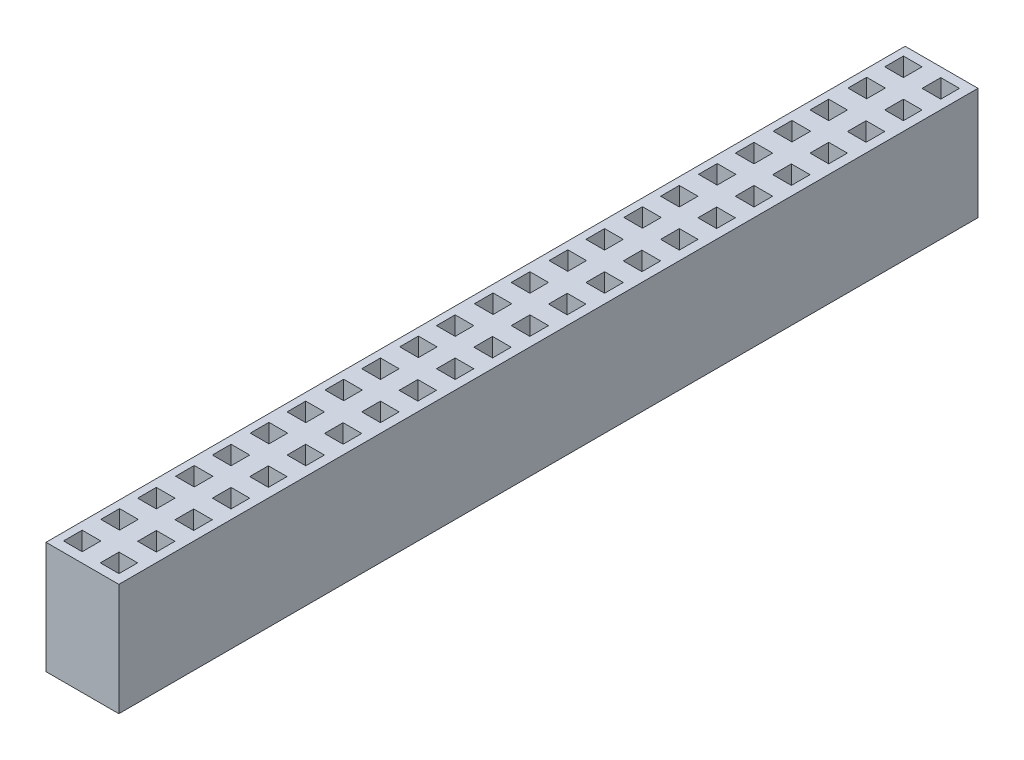
SolidWorks part; units mm, degrees
ref_plane "Front Plane" through (0, 0, 0) normal (0, 0, 1) x (1, 0, 0)
ref_plane "Top Plane" through (0, 0, 0) normal (0, 1, 0) x (1, 0, 0)
ref_plane "Right Plane" through (0, 0, 0) normal (1, 0, 0) x (0, 0, -1)
sketch "Sketch1" plane through (0, 0, 0) normal (0, 1, 0) x (1, 0, 0)
  line L0 (3.0564, 57.785) -> (4.3264, 57.785)
  line L1 (0, 0) -> (4.953, 0)
  line L2 (0, 0) -> (0, 58.42)
  line L3 (0, 58.42) -> (4.953, 58.42)
  line L4 (4.953, 0) -> (4.953, 58.42)
  line L5 (0.5164, 57.785) -> (1.7864, 57.785)
  line L6 (0.5164, 57.785) -> (0.5164, 56.515)
  line L7 (0.5164, 56.515) -> (1.7864, 56.515)
  line L8 (1.7864, 57.785) -> (1.7864, 56.515)
  line L9 (3.0564, 57.785) -> (3.0564, 56.515)
  line L10 (3.0564, 56.515) -> (4.3264, 56.515)
  line L11 (4.3264, 57.785) -> (4.3264, 56.515)
  line L12 (3.0564, 55.245) -> (4.3264, 55.245)
  line L13 (0.5164, 55.2839) -> (1.7864, 55.2839)
  line L14 (0.5164, 55.2839) -> (0.5164, 54.0139)
  line L15 (0.5164, 54.0139) -> (1.7864, 54.0139)
  line L16 (1.7864, 55.2839) -> (1.7864, 54.0139)
  line L17 (3.0564, 55.245) -> (3.0564, 53.975)
  line L18 (3.0564, 53.975) -> (4.3264, 53.975)
  line L19 (4.3264, 55.245) -> (4.3264, 53.975)
  line L20 (3.0564, 52.705) -> (4.3264, 52.705)
  line L21 (0.5164, 52.705) -> (1.7864, 52.705)
  line L22 (0.5164, 52.705) -> (0.5164, 51.435)
  line L23 (0.5164, 51.435) -> (1.7864, 51.435)
  line L24 (1.7864, 52.705) -> (1.7864, 51.435)
  line L25 (3.0564, 52.705) -> (3.0564, 51.435)
  line L26 (3.0564, 51.435) -> (4.3264, 51.435)
  line L27 (4.3264, 52.705) -> (4.3264, 51.435)
  line L28 (3.0564, 50.165) -> (4.3264, 50.165)
  line L29 (0.5164, 50.2039) -> (1.7864, 50.2039)
  line L30 (0.5164, 50.2039) -> (0.5164, 48.9339)
  line L31 (0.5164, 48.9339) -> (1.7864, 48.9339)
  line L32 (1.7864, 50.2039) -> (1.7864, 48.9339)
  line L33 (3.0564, 50.165) -> (3.0564, 48.895)
  line L34 (3.0564, 48.895) -> (4.3264, 48.895)
  line L35 (4.3264, 50.165) -> (4.3264, 48.895)
  line L36 (3.0564, 47.625) -> (4.3264, 47.625)
  line L37 (0.5164, 47.625) -> (1.7864, 47.625)
  line L38 (0.5164, 47.625) -> (0.5164, 46.355)
  line L39 (0.5164, 46.355) -> (1.7864, 46.355)
  line L40 (1.7864, 47.625) -> (1.7864, 46.355)
  line L41 (3.0564, 47.625) -> (3.0564, 46.355)
  line L42 (3.0564, 46.355) -> (4.3264, 46.355)
  line L43 (4.3264, 47.625) -> (4.3264, 46.355)
  line L44 (3.0564, 45.085) -> (4.3264, 45.085)
  line L45 (0.5164, 45.1239) -> (1.7864, 45.1239)
  line L46 (0.5164, 45.1239) -> (0.5164, 43.8539)
  line L47 (0.5164, 43.8539) -> (1.7864, 43.8539)
  line L48 (1.7864, 45.1239) -> (1.7864, 43.8539)
  line L49 (3.0564, 45.085) -> (3.0564, 43.815)
  line L50 (3.0564, 43.815) -> (4.3264, 43.815)
  line L51 (4.3264, 45.085) -> (4.3264, 43.815)
  line L52 (3.0564, 42.545) -> (4.3264, 42.545)
  line L53 (0.5164, 42.545) -> (1.7864, 42.545)
  line L54 (0.5164, 42.545) -> (0.5164, 41.275)
  line L55 (0.5164, 41.275) -> (1.7864, 41.275)
  line L56 (1.7864, 42.545) -> (1.7864, 41.275)
  line L57 (3.0564, 42.545) -> (3.0564, 41.275)
  line L58 (3.0564, 41.275) -> (4.3264, 41.275)
  line L59 (4.3264, 42.545) -> (4.3264, 41.275)
  line L60 (3.0564, 40.005) -> (4.3264, 40.005)
  line L61 (0.5164, 40.0439) -> (1.7864, 40.0439)
  line L62 (0.5164, 40.0439) -> (0.5164, 38.7739)
  line L63 (0.5164, 38.7739) -> (1.7864, 38.7739)
  line L64 (1.7864, 40.0439) -> (1.7864, 38.7739)
  line L65 (3.0564, 40.005) -> (3.0564, 38.735)
  line L66 (3.0564, 38.735) -> (4.3264, 38.735)
  line L67 (4.3264, 40.005) -> (4.3264, 38.735)
  line L68 (3.0564, 37.465) -> (4.3264, 37.465)
  line L69 (0.5164, 37.465) -> (1.7864, 37.465)
  line L70 (0.5164, 37.465) -> (0.5164, 36.195)
  line L71 (0.5164, 36.195) -> (1.7864, 36.195)
  line L72 (1.7864, 37.465) -> (1.7864, 36.195)
  line L73 (3.0564, 37.465) -> (3.0564, 36.195)
  line L74 (3.0564, 36.195) -> (4.3264, 36.195)
  line L75 (4.3264, 37.465) -> (4.3264, 36.195)
  line L76 (3.0564, 34.925) -> (4.3264, 34.925)
  line L77 (0.5164, 34.9639) -> (1.7864, 34.9639)
  line L78 (0.5164, 34.9639) -> (0.5164, 33.6939)
  line L79 (0.5164, 33.6939) -> (1.7864, 33.6939)
  line L80 (1.7864, 34.9639) -> (1.7864, 33.6939)
  line L81 (3.0564, 34.925) -> (3.0564, 33.655)
  line L82 (3.0564, 33.655) -> (4.3264, 33.655)
  line L83 (4.3264, 34.925) -> (4.3264, 33.655)
  line L84 (3.0564, 32.385) -> (4.3264, 32.385)
  line L85 (0.5164, 32.385) -> (1.7864, 32.385)
  line L86 (0.5164, 32.385) -> (0.5164, 31.115)
  line L87 (0.5164, 31.115) -> (1.7864, 31.115)
  line L88 (1.7864, 32.385) -> (1.7864, 31.115)
  line L89 (3.0564, 32.385) -> (3.0564, 31.115)
  line L90 (3.0564, 31.115) -> (4.3264, 31.115)
  line L91 (4.3264, 32.385) -> (4.3264, 31.115)
  line L92 (3.0564, 29.845) -> (4.3264, 29.845)
  line L93 (0.5164, 29.8839) -> (1.7864, 29.8839)
  line L94 (0.5164, 29.8839) -> (0.5164, 28.6139)
  line L95 (0.5164, 28.6139) -> (1.7864, 28.6139)
  line L96 (1.7864, 29.8839) -> (1.7864, 28.6139)
  line L97 (3.0564, 29.845) -> (3.0564, 28.575)
  line L98 (3.0564, 28.575) -> (4.3264, 28.575)
  line L99 (4.3264, 29.845) -> (4.3264, 28.575)
  line L100 (3.0564, 27.305) -> (4.3264, 27.305)
  line L101 (0.5164, 27.305) -> (1.7864, 27.305)
  line L102 (0.5164, 27.305) -> (0.5164, 26.035)
  line L103 (0.5164, 26.035) -> (1.7864, 26.035)
  line L104 (1.7864, 27.305) -> (1.7864, 26.035)
  line L105 (3.0564, 27.305) -> (3.0564, 26.035)
  line L106 (3.0564, 26.035) -> (4.3264, 26.035)
  line L107 (4.3264, 27.305) -> (4.3264, 26.035)
  line L108 (3.0564, 24.765) -> (4.3264, 24.765)
  line L109 (0.5164, 24.8039) -> (1.7864, 24.8039)
  line L110 (0.5164, 24.8039) -> (0.5164, 23.5339)
  line L111 (0.5164, 23.5339) -> (1.7864, 23.5339)
  line L112 (1.7864, 24.8039) -> (1.7864, 23.5339)
  line L113 (3.0564, 24.765) -> (3.0564, 23.495)
  line L114 (3.0564, 23.495) -> (4.3264, 23.495)
  line L115 (4.3264, 24.765) -> (4.3264, 23.495)
  line L116 (3.0564, 22.225) -> (4.3264, 22.225)
  line L117 (0.5164, 22.225) -> (1.7864, 22.225)
  line L118 (0.5164, 22.225) -> (0.5164, 20.955)
  line L119 (0.5164, 20.955) -> (1.7864, 20.955)
  line L120 (1.7864, 22.225) -> (1.7864, 20.955)
  line L121 (3.0564, 22.225) -> (3.0564, 20.955)
  line L122 (3.0564, 20.955) -> (4.3264, 20.955)
  line L123 (4.3264, 22.225) -> (4.3264, 20.955)
  line L124 (3.0564, 19.685) -> (4.3264, 19.685)
  line L125 (0.5164, 19.7239) -> (1.7864, 19.7239)
  line L126 (0.5164, 19.7239) -> (0.5164, 18.4539)
  line L127 (0.5164, 18.4539) -> (1.7864, 18.4539)
  line L128 (1.7864, 19.7239) -> (1.7864, 18.4539)
  line L129 (3.0564, 19.685) -> (3.0564, 18.415)
  line L130 (3.0564, 18.415) -> (4.3264, 18.415)
  line L131 (4.3264, 19.685) -> (4.3264, 18.415)
  line L132 (3.0564, 17.145) -> (4.3264, 17.145)
  line L133 (0.5164, 17.145) -> (1.7864, 17.145)
  line L134 (0.5164, 17.145) -> (0.5164, 15.875)
  line L135 (0.5164, 15.875) -> (1.7864, 15.875)
  line L136 (1.7864, 17.145) -> (1.7864, 15.875)
  line L137 (3.0564, 17.145) -> (3.0564, 15.875)
  line L138 (3.0564, 15.875) -> (4.3264, 15.875)
  line L139 (4.3264, 17.145) -> (4.3264, 15.875)
  line L140 (3.0564, 14.605) -> (4.3264, 14.605)
  line L141 (0.5164, 14.6439) -> (1.7864, 14.6439)
  line L142 (0.5164, 14.6439) -> (0.5164, 13.3739)
  line L143 (0.5164, 13.3739) -> (1.7864, 13.3739)
  line L144 (1.7864, 14.6439) -> (1.7864, 13.3739)
  line L145 (3.0564, 14.605) -> (3.0564, 13.335)
  line L146 (3.0564, 13.335) -> (4.3264, 13.335)
  line L147 (4.3264, 14.605) -> (4.3264, 13.335)
  line L148 (3.0564, 12.065) -> (4.3264, 12.065)
  line L149 (0.5164, 12.065) -> (1.7864, 12.065)
  line L150 (0.5164, 12.065) -> (0.5164, 10.795)
  line L151 (0.5164, 10.795) -> (1.7864, 10.795)
  line L152 (1.7864, 12.065) -> (1.7864, 10.795)
  line L153 (3.0564, 12.065) -> (3.0564, 10.795)
  line L154 (3.0564, 10.795) -> (4.3264, 10.795)
  line L155 (4.3264, 12.065) -> (4.3264, 10.795)
  line L156 (3.0564, 9.525) -> (4.3264, 9.525)
  line L157 (0.5164, 9.5639) -> (1.7864, 9.5639)
  line L158 (0.5164, 9.5639) -> (0.5164, 8.2939)
  line L159 (0.5164, 8.2939) -> (1.7864, 8.2939)
  line L160 (1.7864, 9.5639) -> (1.7864, 8.2939)
  line L161 (3.0564, 9.525) -> (3.0564, 8.255)
  line L162 (3.0564, 8.255) -> (4.3264, 8.255)
  line L163 (4.3264, 9.525) -> (4.3264, 8.255)
  line L164 (3.0564, 6.985) -> (4.3264, 6.985)
  line L165 (0.5164, 6.985) -> (1.7864, 6.985)
  line L166 (0.5164, 6.985) -> (0.5164, 5.715)
  line L167 (0.5164, 5.715) -> (1.7864, 5.715)
  line L168 (1.7864, 6.985) -> (1.7864, 5.715)
  line L169 (3.0564, 6.985) -> (3.0564, 5.715)
  line L170 (3.0564, 5.715) -> (4.3264, 5.715)
  line L171 (4.3264, 6.985) -> (4.3264, 5.715)
  line L172 (3.0564, 4.445) -> (4.3264, 4.445)
  line L173 (0.5164, 4.4839) -> (1.7864, 4.4839)
  line L174 (0.5164, 4.4839) -> (0.5164, 3.2139)
  line L175 (0.5164, 3.2139) -> (1.7864, 3.2139)
  line L176 (1.7864, 4.4839) -> (1.7864, 3.2139)
  line L177 (3.0564, 4.445) -> (3.0564, 3.175)
  line L178 (3.0564, 3.175) -> (4.3264, 3.175)
  line L179 (4.3264, 4.445) -> (4.3264, 3.175)
  line L180 (3.0564, 1.905) -> (4.3264, 1.905)
  line L181 (0.5164, 1.9439) -> (1.7864, 1.9439)
  line L182 (0.5164, 1.9439) -> (0.5164, 0.6739)
  line L183 (0.5164, 0.6739) -> (1.7864, 0.6739)
  line L184 (1.7864, 1.9439) -> (1.7864, 0.6739)
  line L185 (3.0564, 1.905) -> (3.0564, 0.635)
  line L186 (3.0564, 0.635) -> (4.3264, 0.635)
  line L187 (4.3264, 1.905) -> (4.3264, 0.635)
  dimension "D1" = 58.42
  dimension "D2" = 4.953
  dimension "D3" = 1.27
  dimension "D4" = 1.27
  dimension "D5" = 1.27
  dimension "D6" = 1.27
  dimension "D7" = 1.27
  dimension "D8" = 0.635
  dimension "D9" = 1.27
  dimension "D10" = 1.27
  dimension "D11" = 1.27
  dimension "D12" = 1.27
  dimension "D13" = 1.27
  dimension "D14" = 1.27
  dimension "D15" = 1.27
  dimension "D16" = 1.27
  dimension "D17" = 1.27
  dimension "D18" = 1.27
  dimension "D19" = 1.27
  dimension "D20" = 1.27
  dimension "D21" = 1.27
  dimension "D22" = 1.27
  dimension "D23" = 1.27
  dimension "D24" = 1.27
  dimension "D25" = 1.27
  dimension "D26" = 1.27
  dimension "D27" = 1.27
  dimension "D28" = 1.27
  dimension "D29" = 1.27
  dimension "D30" = 1.27
  dimension "D31" = 1.27
  dimension "D32" = 1.27
  dimension "D33" = 1.27
  dimension "D34" = 1.27
  dimension "D35" = 1.27
  dimension "D36" = 1.27
  dimension "D37" = 1.27
  dimension "D38" = 1.27
  dimension "D39" = 1.27
  dimension "D40" = 1.27
  dimension "D41" = 1.27
  dimension "D42" = 1.27
  dimension "D43" = 1.27
  dimension "D44" = 1.27
  dimension "D45" = 1.27
  dimension "D46" = 1.27
  dimension "D47" = 1.27
  dimension "D48" = 1.27
  dimension "D49" = 1.27
  dimension "D50" = 1.27
  dimension "D51" = 1.27
  dimension "D52" = 1.27
  dimension "D53" = 1.27
  dimension "D54" = 1.27
  dimension "D55" = 1.27
  dimension "D56" = 1.27
  dimension "D57" = 1.27
  dimension "D58" = 1.27
  dimension "D59" = 1.27
  dimension "D60" = 1.27
  dimension "D61" = 1.27
  dimension "D62" = 1.27
  dimension "D63" = 1.27
  dimension "D64" = 1.27
  dimension "D65" = 1.27
  dimension "D66" = 1.27
  dimension "D67" = 1.27
  dimension "D68" = 1.27
  dimension "D69" = 1.27
  dimension "D70" = 1.27
  dimension "D71" = 1.27
  dimension "D72" = 1.27
  dimension "D73" = 1.27
  dimension "D74" = 1.27
  dimension "D75" = 1.27
  dimension "D76" = 1.27
  dimension "D77" = 1.27
  dimension "D78" = 1.27
  dimension "D79" = 1.27
  dimension "D80" = 1.27
  dimension "D81" = 1.27
  dimension "D82" = 1.27
  dimension "D83" = 1.27
  dimension "D84" = 1.27
  dimension "D85" = 1.27
  dimension "D86" = 1.27
  dimension "D87" = 1.27
  dimension "D88" = 1.27
  dimension "D89" = 1.27
  dimension "D90" = 1.27
  dimension "D91" = 1.27
  dimension "D92" = 1.27
  dimension "D93" = 1.27
  dimension "D94" = 1.27
  dimension "D95" = 1.27
  dimension "D96" = 1.27
  dimension "D97" = 1.27
  dimension "D98" = 1.27
  dimension "D99" = 1.27
  dimension "D100" = 1.27
  dimension "D101" = 1.27
  dimension "D102" = 1.27
  dimension "D103" = 1.27
  dimension "D104" = 1.27
  dimension "D105" = 1.27
  dimension "D106" = 1.27
  dimension "D107" = 1.27
  dimension "D108" = 1.27
  dimension "D109" = 1.27
  dimension "D110" = 1.27
  dimension "D111" = 1.27
  dimension "D112" = 1.27
  dimension "D113" = 1.27
  dimension "D114" = 1.27
  dimension "D115" = 1.27
  dimension "D116" = 1.27
  dimension "D117" = 1.27
  dimension "D118" = 1.27
  dimension "D119" = 1.27
  dimension "D120" = 1.27
  dimension "D121" = 1.27
  dimension "D122" = 1.27
  dimension "D123" = 1.27
  dimension "D124" = 1.27
  dimension "D125" = 1.27
  dimension "D126" = 1.27
  dimension "D127" = 1.27
  dimension "D128" = 1.27
  dimension "D129" = 1.27
  dimension "D130" = 1.27
  dimension "D131" = 1.27
  dimension "D132" = 1.27
  dimension "D133" = 1.27
  dimension "D134" = 1.27
  dimension "D135" = 1.27
  dimension "D136" = 1.27
  dimension "D137" = 1.27
  dimension "D138" = 1.27
  dimension "D139" = 1.27
  dimension "D140" = 1.27
  dimension "D141" = 1.27
  dimension "D142" = 1.27
  dimension "D143" = 1.27
  dimension "D144" = 1.27
  dimension "D145" = 1.27
  dimension "D146" = 1.27
  dimension "D147" = 1.27
  dimension "D148" = 1.27
  dimension "D149" = 1.27
  dimension "D150" = 1.27
  dimension "D151" = 1.27
  dimension "D152" = 1.27
  dimension "D153" = 1.27
  dimension "D154" = 1.27
  dimension "D155" = 1.27
  dimension "D156" = 1.27
  dimension "D157" = 1.27
  dimension "D158" = 1.27
  dimension "D159" = 1.27
  dimension "D160" = 1.27
  dimension "D161" = 1.27
  dimension "D162" = 1.27
  dimension "D163" = 1.27
  dimension "D164" = 1.27
  dimension "D165" = 1.27
  dimension "D166" = 1.27
  dimension "D167" = 1.27
  dimension "D168" = 1.27
  dimension "D169" = 1.27
  dimension "D170" = 1.27
  dimension "D171" = 1.27
  dimension "D172" = 1.27
  dimension "D173" = 1.27
  dimension "D174" = 0.635
extrude "Boss-Extrude1" add sketch "Sketch1" along normal blind 7.62
